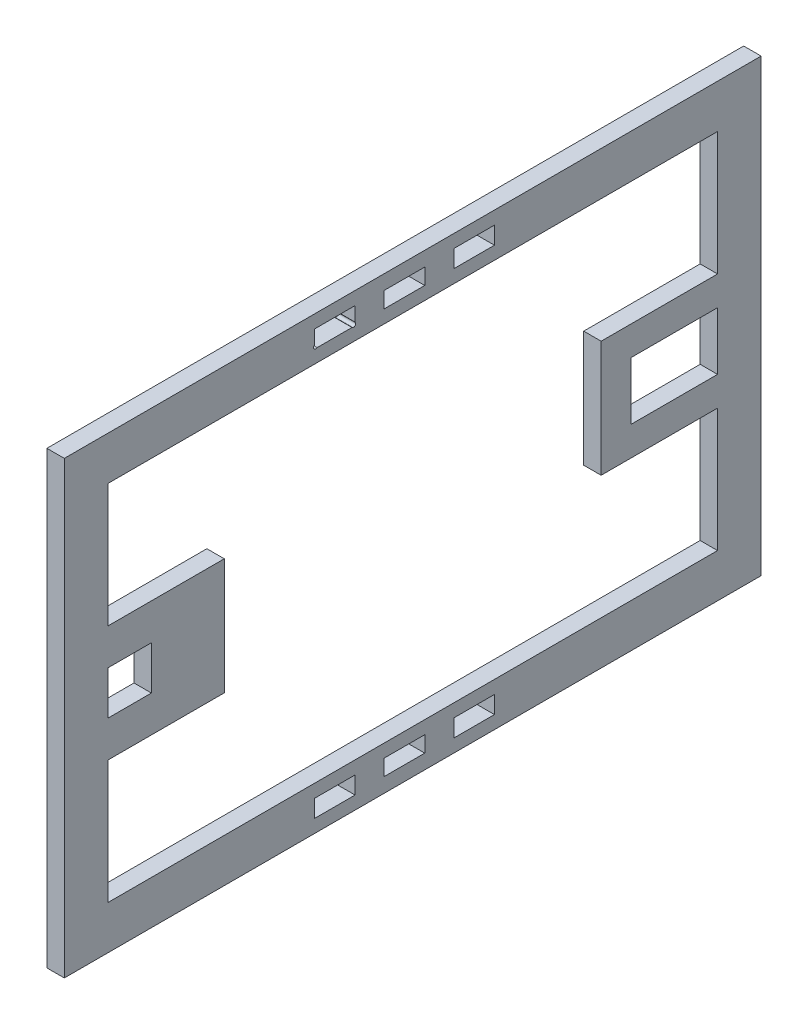
SolidWorks part; units mm, degrees
ref_plane "Alzado" through (0, 0, 0) normal (0, 0, 1) x (1, 0, 0)
ref_plane "Planta" through (0, 0, 0) normal (0, 1, 0) x (1, 0, 0)
ref_plane "Vista lateral" through (0, 0, 0) normal (1, 0, 0) x (0, 0, -1)
sketch "Croquis1" plane through (0, 0, 0) normal (1, 0, 0) x (0, 0, -1)
  line L0 (30, -30) -> (450, -30)
  line L1 (0, 0) -> (480, 0)
  line L2 (0, 0) -> (0, -310)
  line L3 (0, -310) -> (480, -310)
  line L4 (480, 0) -> (480, -310)
  line L5 (30, -155) -> (450, -155) construction
  line L6 (30, -280) -> (450, -280)
  line L7 (30, -30) -> (30, -115)
  line L8 (296.3003, -301) -> (296.3003, -289)
  line L9 (268.3003, -289) -> (296.3003, -289)
  line L10 (248.3003, -300) -> (248.3003, -289)
  line L11 (220.3003, -289) -> (248.3003, -289)
  line L12 (220.3003, -300) -> (220.3003, -289)
  line L13 (220.3003, -300) -> (248.3003, -300)
  line L14 (268.3003, -301) -> (268.3003, -289)
  line L15 (268.3003, -301) -> (296.3003, -301)
  line L16 (200.3003, -301) -> (200.3003, -289)
  line L17 (172.3003, -289) -> (200.3003, -289)
  line L18 (172.3003, -301) -> (172.3003, -289)
  line L19 (172.3003, -301) -> (200.3003, -301)
  line L20 (450, -115) -> (369.8, -115)
  line L21 (172.3003, -9) -> (200.3003, -9)
  line L22 (172.3003, -9) -> (172.3003, -21)
  line L23 (172.3003, -21) -> (200.3003, -21)
  line L24 (200.3003, -9) -> (200.3003, -21)
  line L25 (268.3003, -9) -> (296.3003, -9)
  line L26 (268.3003, -9) -> (268.3003, -21)
  line L27 (220.3003, -10) -> (248.3003, -10)
  line L28 (220.3003, -10) -> (220.3003, -21)
  line L29 (220.3003, -21) -> (248.3003, -21)
  line L30 (248.3003, -10) -> (248.3003, -21)
  line L31 (268.3003, -21) -> (296.3003, -21)
  line L32 (296.3003, -9) -> (296.3003, -21)
  line L33 (450, -30) -> (450, -115)
  line L34 (369.8, -115) -> (369.8, -195)
  line L35 (450, -195) -> (369.8, -195)
  line L36 (60, -170) -> (30, -170)
  line L37 (450, -30) -> (450, -280) construction
  line L38 (390.45, -135.1) -> (450, -135.1)
  line L39 (390.45, -135.1) -> (390.45, -174.9)
  line L40 (450, -195) -> (450, -280)
  line L41 (390.45, -174.9) -> (450, -174.9)
  line L42 (450, -135.1) -> (450, -174.9)
  line L43 (30, -195) -> (110.2, -195)
  line L44 (30, -115) -> (110.2, -115)
  line L45 (60, -170) -> (60, -140)
  line L46 (60, -140) -> (30, -140)
  line L47 (110.2, -195) -> (110.2, -115)
  line L49 (30, -140) -> (30, -170)
  line L50 (30, -30) -> (30, -280) construction
  line L51 (30, -195) -> (30, -280)
  point P40 (369.8, -155)
  point P49 (110.2, -155)
  point P54 (60, -155)
  dimension "D1" = 30
  dimension "D2" = 155
  dimension "D3" = 310
  dimension "D4" = 40
  dimension "D5" = 480
  dimension "D6" = 80.2
  dimension "D7" = 183.6997
  dimension "D8" = 28
  dimension "D9" = 20.1
  dimension "D10" = 9
  dimension "D11" = 9
  dimension "D12" = 10
  dimension "D13" = 9
  dimension "D14" = 20
  dimension "D15" = 20
  dimension "D16" = 9
  dimension "D17" = 9
  dimension "D18" = 28
  dimension "D19" = 28
  dimension "D20" = 20.65
  dimension "D21" = 30
  dimension "D22" = 20.1
  dimension "D23" = 15
  dimension "D25" = 25
  dimension "D26" = 125
  dimension "D27" = 40
  dimension "D28" = 80
  dimension "D29" = 80.2
extrude "Saliente-Extruir1" add sketch "Croquis1" along normal blind 12 contours L1 L4 L3 L2
sketch "Croquis6" plane through (12, 0, 0) normal (1, 0, 0) x (0, 0, -1)
  line L0 (172.3003, -21) -> (173.2411, -19.8317) construction
  line L1 (172.3003, -21) -> (200.3003, -21) construction
  line L2 (200.3003, -21) -> (199.2397, -19.9393) construction
  line L3 (172.3003, -9) -> (172.3003, -21) construction
  circle A0 centre (173.2411, -19.8317) radius 1.5
  circle A1 centre (199.2397, -19.9393) radius 1.5
  dimension "D6" = 3
  dimension "D1" = 3
  dimension "D2" = 1.5
  dimension "D4" = 45
  dimension "D5" = 1.5
extrude "Cortar-Extruir2" cut sketch "Croquis6" against normal blind 12
